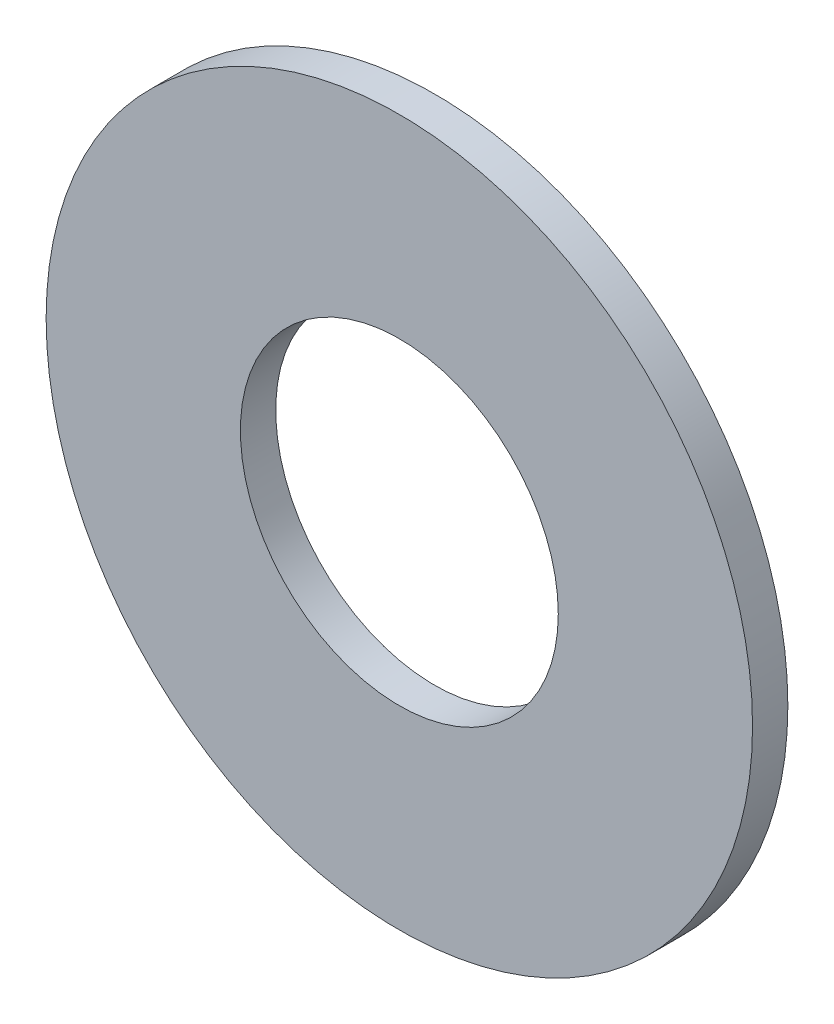
SolidWorks part; units mm, degrees
ref_plane "Front Plane" through (0, 0, 0) normal (0, 0, 1) x (1, 0, 0)
ref_plane "Top Plane" through (0, 0, 0) normal (0, 1, 0) x (1, 0, 0)
ref_plane "Right Plane" through (0, 0, 0) normal (1, 0, 0) x (0, 0, -1)
sketch "Sketch1" plane through (0, 0, 0) normal (0, 0, 1) x (1, 0, 0)
  circle A0 centre (0, 0) radius 10
  circle A1 centre (0, 0) radius 4.5
  dimension "D1" = 9
  dimension "D2" = 20
extrude "Boss-Extrude1" add sketch "Sketch1" against normal blind 1
